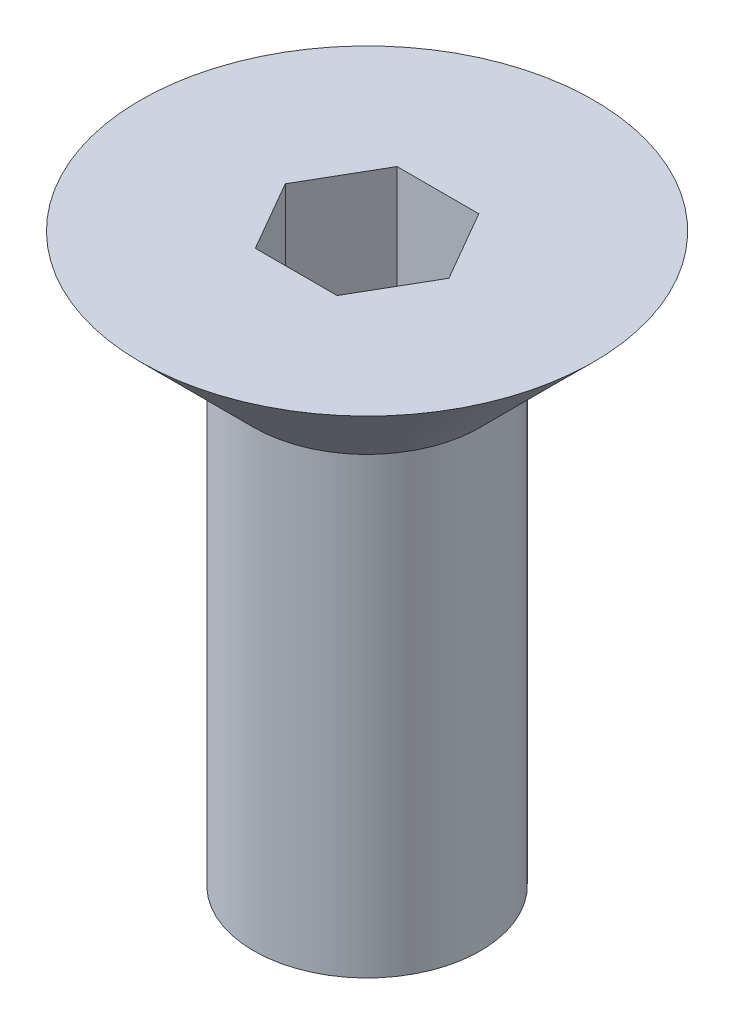
SolidWorks part; units mm, degrees
material "AISI 304"
ref_plane "Front Plane" through (0, 0, 0) normal (0, 0, 1) x (1, 0, 0)
ref_plane "Top Plane" through (0, 0, 0) normal (0, 1, 0) x (1, 0, 0)
ref_plane "Right Plane" through (0, 0, 0) normal (1, 0, 0) x (0, 0, -1)
sketch "Sketch1" plane through (0, 0, 0) normal (0, 0, 1) x (1, 0, 0)
  line L0 (0, 61.6916) -> (0, -59.3578) construction
  line L1 (0, -20) -> (4, -20)
  line L2 (4, -20) -> (4, -4)
  line L3 (-5.7326, -2.2674) -> (-4, -4) construction
  line L5 (8, 0) -> (0, 0)
  line L6 (0, 0) -> (0, -20)
  line L7 (4, -4) -> (8, 0)
  dimension "D1" = 90
  dimension "D2" = 16
  dimension "D3" = 8
  dimension "D5" = 20
revolve "Revolve1" add sketch "Sketch1" angle 360 about L0
sketch "Sketch2" plane through (0, 0, 0) normal (0, 1, 0) x (-1, 0, 0)
  line L1 (-1.4434, -2.5) -> (1.4434, -2.5)
  line L2 (1.4434, -2.5) -> (2.8868, 0)
  line L3 (2.8868, 0) -> (1.4434, 2.5)
  line L4 (1.4434, 2.5) -> (-1.4434, 2.5)
  line L5 (-1.4434, 2.5) -> (-2.8868, 0)
  line L6 (-2.8868, 0) -> (-1.4434, -2.5)
  circle A0 centre (0, 0) radius 2.5 construction
  dimension "D1" = 5
extrude "Cut-Extrude1" cut sketch "Sketch2" against normal blind 5
